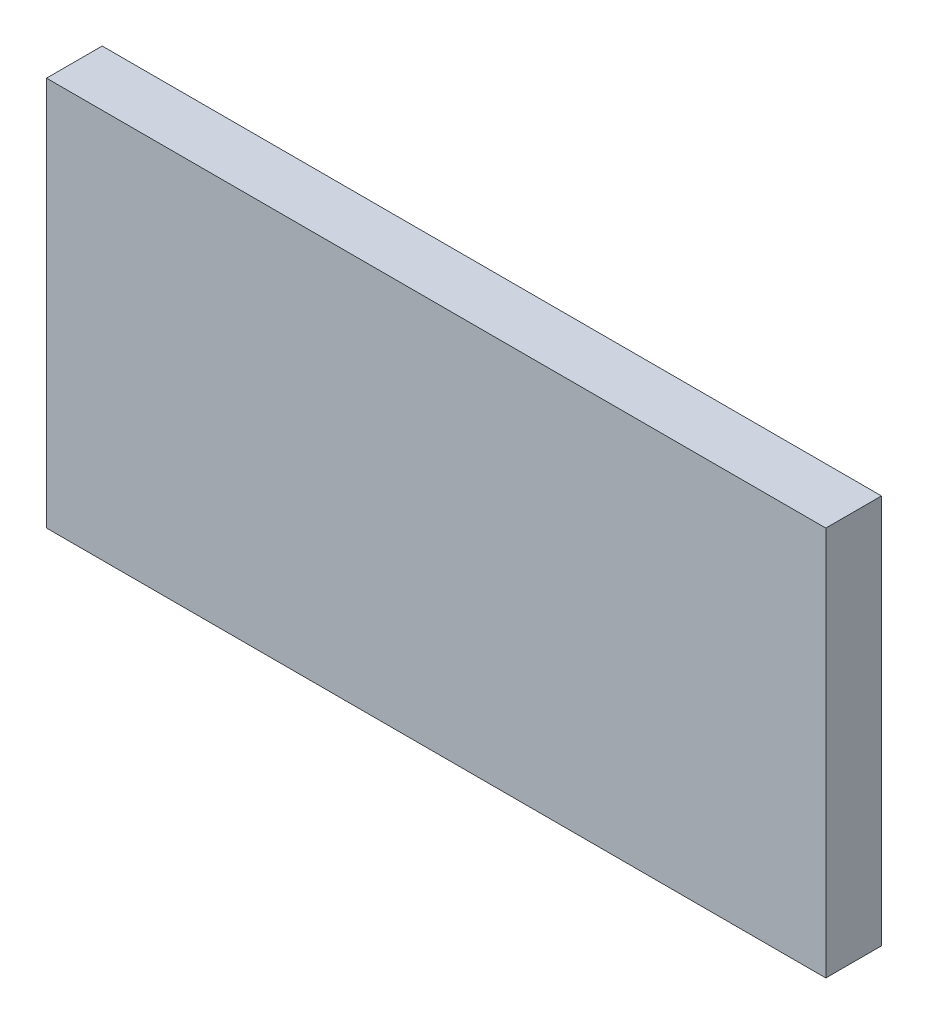
SolidWorks part; units mm, degrees
ref_plane "Front Plane" through (0, 0, 0) normal (0, 0, 1) x (1, 0, 0)
ref_plane "Top Plane" through (0, 0, 0) normal (0, 1, 0) x (1, 0, 0)
ref_plane "Right Plane" through (0, 0, 0) normal (1, 0, 0) x (0, 0, -1)
sketch "Sketch1" plane through (0, 0, 0) normal (0, 0, 1) x (1, 0, 0)
  line L1 (-17.78, -8.89) -> (17.78, -8.89)
  line L2 (-17.78, -8.89) -> (-17.78, 8.89)
  line L3 (-17.78, 8.89) -> (17.78, 8.89)
  line L4 (17.78, -8.89) -> (17.78, 8.89)
  line L5 (-17.78, -8.89) -> (17.78, 8.89) construction
  line L6 (-17.78, 8.89) -> (17.78, -8.89) construction
  point P0 (0, 0)
  dimension "D1" = 35.56
  dimension "D2" = 17.78
extrude "Boss-Extrude1" add sketch "Sketch1" along normal blind 2.54
